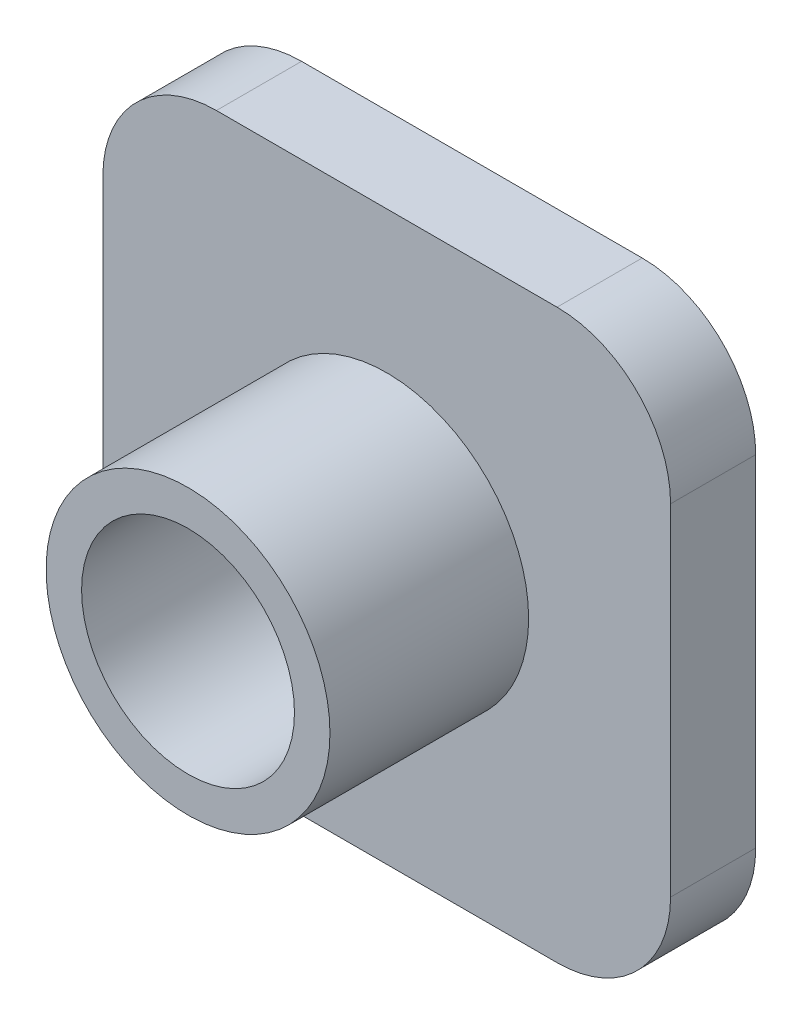
SolidWorks part; units mm, degrees
ref_plane "Front Plane" through (0, 0, 0) normal (0, 0, 1) x (1, 0, 0)
ref_plane "Top Plane" through (0, 0, 0) normal (0, 1, 0) x (1, 0, 0)
ref_plane "Right Plane" through (0, 0, 0) normal (1, 0, 0) x (0, 0, -1)
sketch "Sketch1" plane through (0, 0, 0) normal (0, 0, 1) x (1, 0, 0)
  circle A0 centre (-123, -48) radius 10
  circle A1 centre (-123, -48) radius 7.5
extrude "Boss-Extrude1" add sketch "Sketch1" along normal blind 20
sketch "Sketch2" plane through (0, 0, 0) normal (0, 0, -1) x (-1, 0, 0)
  line L9 (111, -28) -> (135, -28)
  line L10 (103, -36) -> (103, -60)
  line L11 (111, -68) -> (135, -68)
  line L12 (143, -36) -> (143, -60)
  circle A11 centre (123, -21.75) radius 6.5 construction
  circle A12 centre (123, -48) radius 10 construction
  arc A13 (135, -28) -> (143, -36) centre (135, -36) cw
  arc A14 (135, -68) -> (143, -60) centre (135, -60) ccw
  arc A15 (103, -60) -> (111, -68) centre (111, -60) ccw
  arc A16 (111, -28) -> (103, -36) centre (111, -36) ccw
  circle A17 centre (123, -48) radius 7.5 construction
  circle A18 centre (123, -48) radius 7.5
  point P11 (143, -28)
  point P16 (103, -68)
  point P19 (103, -28)
  dimension "D1" = 20
  dimension "D5" = 8
  dimension "D2" = 40
  dimension "D3" = 20
  dimension "D4" = 40
extrude "Boss-Extrude2" add sketch "Sketch2" against normal blind 6
